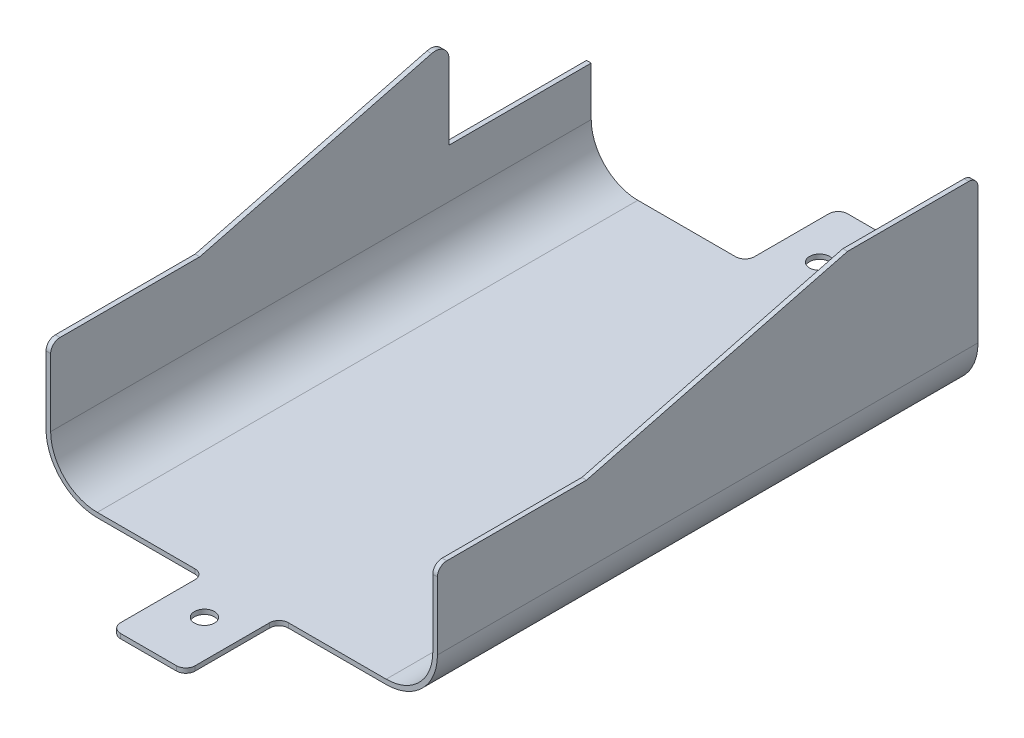
SolidWorks part; units mm, degrees
ref_plane "Front Plane" through (0, 0, 0) normal (0, 0, 1) x (1, 0, 0)
ref_plane "Top Plane" through (0, 0, 0) normal (0, 1, 0) x (1, 0, 0)
ref_plane "Right Plane" through (0, 0, 0) normal (1, 0, 0) x (0, 0, -1)
sketch "Sketch1" plane through (0, 0, 0) normal (0, 0, 1) x (1, 0, 0)
  line L4 (-31, -27.5) -> (31, -27.5)
  line L5 (-40, 18.5) -> (-40, -18.5)
  line L6 (31, 27.5) -> (-31, 27.5)
  line L7 (40, -18.5) -> (40, 18.5)
  line L8 (-31, -27.5) -> (31, -27.5)
  line L9 (-40, 18.5) -> (-40, -18.5)
  line L10 (31, 27.5) -> (-31, 27.5)
  line L11 (40, -18.5) -> (40, 18.5)
  line L12 (-31, -29.5) -> (31, -29.5)
  line L13 (42, -18.5) -> (42, 18.5)
  line L14 (31, 29.5) -> (-31, 29.5)
  line L15 (-42, 18.5) -> (-42, -18.5)
  line L16 (-31, -29.5) -> (31, -29.5)
  line L17 (42, -18.5) -> (42, 18.5)
  line L18 (31, 29.5) -> (-31, 29.5)
  line L19 (-42, 18.5) -> (-42, -18.5)
  line L20 (-41, 18.5) -> (-41, -18.5)
  line L21 (-31, -28.5) -> (31, -28.5)
  line L22 (41, -18.5) -> (41, 18.5)
  line L23 (31, 28.5) -> (-31, 28.5)
  line L24 (-41, 18.5) -> (-41, -18.5)
  line L25 (-31, -28.5) -> (31, -28.5)
  line L26 (41, -18.5) -> (41, 18.5)
  line L27 (31, 28.5) -> (-31, 28.5)
  arc A4 (31, -27.5) -> (40, -18.5) centre (31, -18.5) ccw
  arc A5 (-40, -18.5) -> (-31, -27.5) centre (-31, -18.5) ccw
  arc A6 (-31, 27.5) -> (-40, 18.5) centre (-31, 18.5) ccw
  arc A7 (40, 18.5) -> (31, 27.5) centre (31, 18.5) ccw
  arc A8 (31, -27.5) -> (40, -18.5) centre (31, -18.5) ccw
  arc A9 (-40, -18.5) -> (-31, -27.5) centre (-31, -18.5) ccw
  arc A10 (-31, 27.5) -> (-40, 18.5) centre (-31, 18.5) ccw
  arc A11 (40, 18.5) -> (31, 27.5) centre (31, 18.5) ccw
  arc A12 (31, -29.5) -> (42, -18.5) centre (31, -18.5) ccw
  arc A13 (42, 18.5) -> (31, 29.5) centre (31, 18.5) ccw
  arc A14 (-31, 29.5) -> (-42, 18.5) centre (-31, 18.5) ccw
  arc A15 (-42, -18.5) -> (-31, -29.5) centre (-31, -18.5) ccw
  arc A16 (31, -29.5) -> (42, -18.5) centre (31, -18.5) ccw
  arc A17 (42, 18.5) -> (31, 29.5) centre (31, 18.5) ccw
  arc A18 (-31, 29.5) -> (-42, 18.5) centre (-31, 18.5) ccw
  arc A19 (-42, -18.5) -> (-31, -29.5) centre (-31, -18.5) ccw
  arc A20 (-41, -18.5) -> (-31, -28.5) centre (-31, -18.5) ccw
  arc A21 (31, -28.5) -> (41, -18.5) centre (31, -18.5) ccw
  arc A22 (41, 18.5) -> (31, 28.5) centre (31, 18.5) ccw
  arc A23 (-31, 28.5) -> (-41, 18.5) centre (-31, 18.5) ccw
  arc A24 (-41, -18.5) -> (-31, -28.5) centre (-31, -18.5) ccw
  arc A25 (31, -28.5) -> (41, -18.5) centre (31, -18.5) ccw
  arc A26 (41, 18.5) -> (31, 28.5) centre (31, 18.5) ccw
  arc A27 (-31, 28.5) -> (-41, 18.5) centre (-31, 18.5) ccw
  dimension "D1" = 0
  dimension "D2" = 0
  dimension "D3" = 0
extrude "Boss-Extrude1" add sketch "Sketch1" against normal up to surface (116 mm away) contours L19 A19 L16 A16 L17 A17 L18 A18 A27 L27 A26 L26 A25 L25 A24 L24
sketch "Sketch2" plane through (0, -29.5, 0) normal (0, -1, 0) x (1, 0, 0)
  line L0 (-31, 0) -> (31, 0) construction
  line L1 (8, 0) -> (-8, 0)
  line L2 (8, 0) -> (8, 20)
  line L3 (8, 20) -> (-8, 20)
  line L4 (-8, 0) -> (-8, 20)
  line L5 (8, 27.5) -> (8, 0) construction
  line L7 (31, -116) -> (-31, -116) construction
  line L8 (-8, -116) -> (8, -116)
  line L9 (-8, -116) -> (-8, -136)
  line L10 (-8, -136) -> (8, -136)
  line L11 (8, -116) -> (8, -136)
  line L12 (-8, -143.5) -> (-8, -116) construction
  line L13 (8, -116) -> (8, -143.5) construction
  line L14 (-8, 0) -> (-8, 27.5) construction
  dimension "D1" = 20
  dimension "D2" = 20
extrude "Boss-Extrude2" add sketch "Sketch2" against normal blind 1
sketch "Sketch3" plane through (42, 0, 0) normal (1, 0, 0) x (0, 0, -1)
  line L0 (0, -2) -> (32, -2)
  line L1 (0, -18.5) -> (0, 18.5) construction
  line L2 (32, -2) -> (88, 12.5)
  line L3 (88, 12.5) -> (116, 12.5)
  line L4 (116, 18.5) -> (116, -18.5) construction
  line L5 (114, 16.5) -> (91, 16.5) construction
  line L6 (0, -2) -> (0, 29.5)
  line L7 (0, 29.5) -> (116, 29.5)
  line L8 (116, 29.5) -> (116, 12.5)
  line L12 (35, 2) -> (0, 2)
  line L13 (91, 16.5) -> (35, 2)
  line L14 (116, 16.5) -> (91, 16.5)
  line L15 (116, -29.5) -> (116, 16.5)
  line L16 (0, -29.5) -> (116, -29.5)
  line L17 (0, 2) -> (0, -29.5)
  line L19 (91, 16.5) -> (35, 2) construction
  dimension "D1" = 2
  dimension "D2" = 4
  dimension "D4" = 3
  dimension "D3" = 0
extrude "Cut-Extrude1" cut sketch "Sketch3" against normal through all
fillet "Fillet1" radius 2 12 edges at (41.5, 12.5, -116) (8, -29, -116) (8, -29, -136) (-8, -29, -136) (-41.5, 12.5, -116) (-8, -29, -116) (-41.5, -2, 0) (-8, -29, 20) (-8, -29, 0) (8, -29, 20) (8, -29, 0) (41.5, -2, 0)
sketch "Sketch5" plane through (-42, 0, 0) normal (-1, 0, 0) x (0, 0, 1)
  line L0 (-109, 8.5) -> (-89.5, 8.5) construction
  line L1 (-109, 8.5) -> (-89.5, 8.5) construction
  line L2 (-89.5, -4) -> (-109, -4) construction
  line L3 (-89.5, -4) -> (-109, -4) construction
  line L4 (-109, -4) -> (-109, 8.5) construction
  line L5 (-109, -4) -> (-109, 8.5) construction
  line L6 (-89.5, -4) -> (-89.5, 8.5) construction
  line L7 (-113, 12.5) -> (-85.5, 12.5)
  line L8 (-85.5, -8) -> (-85.5, 12.5)
  line L9 (-85.5, -8) -> (-113, -8)
  line L10 (-113, -8) -> (-113, 12.5)
  line L12 (-113, -8) -> (-126.7094, -8)
  line L13 (-113, -8) -> (-113, 12.5)
  line L14 (-113, 12.5) -> (-126.7094, 12.5)
  line L15 (-126.7094, -8) -> (-126.7094, 12.5)
  line M5 (-88, 12.5) -> (-114, 12.5)
  arc M6 (-114, 12.5) -> (-116, 10.5) centre (-114, 10.5) ccw
  line M7 (-116, 10.5) -> (-116, -18.5)
  line M12 (-32, -2) -> (-88, 12.5)
  dimension "D1" = 4
extrude "Cut-Extrude2" cut sketch "Sketch5" against normal up to surface (1 mm away) contours L12 L10 M5 M6 M7 | L10 L9 L8 M12 M5 up to face at (-41, -1.0839, -58.5)
fillet "Fillet2" radius 3 1 edges at (-41.5, 11.8527, -85.5)
sketch "Sketch6" plane through (0, -29.5, 0) normal (0, -1, 0) x (1, 0, 0)
  circle A0 centre (0, -124) radius 2.15 construction
  circle A1 centre (0, -124) radius 2.15
  circle A2 centre (0, 8) radius 2.15 construction
  circle A3 centre (0, 8) radius 2.15
extrude "Cut-Extrude3" cut sketch "Sketch6" against normal up to surface (1 mm away) up to face at (0, -28.5, -58)
